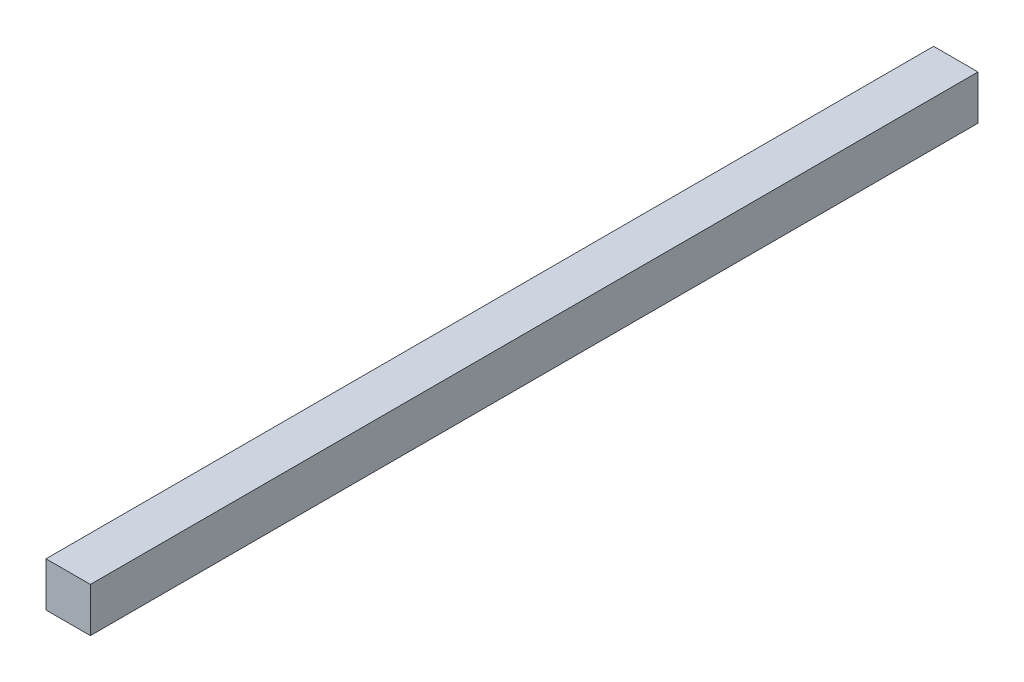
SolidWorks part; units mm, degrees
ref_plane "前视基准面" through (0, 0, 0) normal (0, 0, 1) x (1, 0, 0)
ref_plane "上视基准面" through (0, 0, 0) normal (0, 1, 0) x (1, 0, 0)
ref_plane "右视基准面" through (0, 0, 0) normal (1, 0, 0) x (0, 0, -1)
sketch "草图1" plane through (0, 0, 0) normal (0, 0, 1) x (1, 0, 0)
  line L1 (-5, 5) -> (5, 5)
  line L2 (-5, 5) -> (-5, -5)
  line L3 (-5, -5) -> (5, -5)
  line L4 (5, 5) -> (5, -5)
  line L5 (-5, 5) -> (5, -5) construction
  line L6 (-5, -5) -> (5, 5) construction
  point P0 (0, 0)
  dimension "D1" = 10
  dimension "D2" = 10
extrude "凸台-拉伸1" add sketch "草图1" along normal blind 300 contours L1 L4 L3 L2
sketch "草图2" plane through (0, 0, 0) normal (0, 0, -1) x (-1, 0, 0)
  line L4 (5, -5) -> (5, 5)
  line L5 (5, 5) -> (-5, 5)
  line L6 (-5, 5) -> (-5, -5)
  line L7 (-5, -5) -> (5, -5)
  line L8 (5, -5) -> (5, 5)
  line L9 (5, 5) -> (-5, 5)
  line L10 (-5, 5) -> (-5, -5)
  line L11 (-5, -5) -> (5, -5)
  dimension "D1" = 0
extrude "切除-拉伸1" cut sketch "草图2" against normal blind 100
